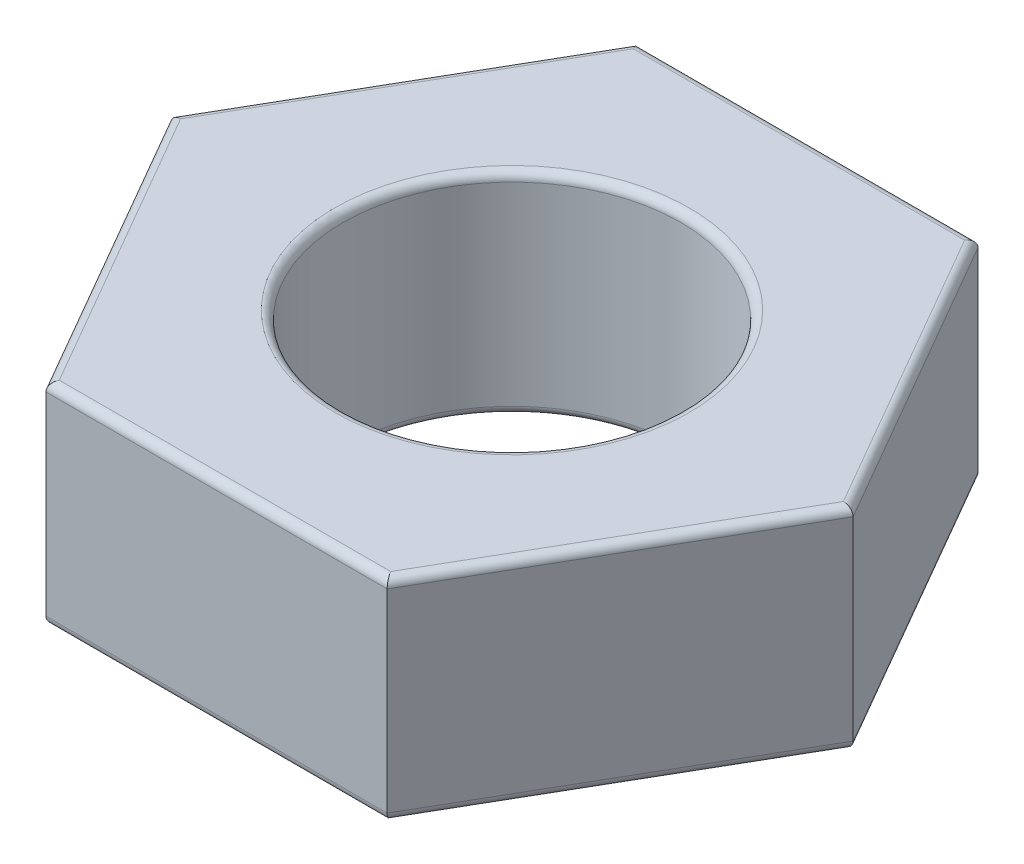
SolidWorks part; units mm, degrees
ref_plane "Front Plane" through (0, 0, 0) normal (0, 0, 1) x (1, 0, 0)
ref_plane "Top Plane" through (0, 0, 0) normal (0, 1, 0) x (1, 0, 0)
ref_plane "Right Plane" through (0, 0, 0) normal (1, 0, 0) x (0, 0, -1)
sketch "Sketch1" plane through (0, 0, 0) normal (0, 1, 0) x (1, 0, 0)
  line L1 (2.0207, -3.5) -> (4.0415, 0)
  line L2 (4.0415, 0) -> (2.0207, 3.5)
  line L3 (2.0207, 3.5) -> (-2.0207, 3.5)
  line L4 (-2.0207, 3.5) -> (-4.0415, 0)
  line L5 (-4.0415, 0) -> (-2.0207, -3.5)
  line L6 (-2.0207, -3.5) -> (2.0207, -3.5)
  circle A0 centre (0, 0) radius 3.5 construction
  circle A1 centre (0, 0) radius 2
  dimension "D1" = 7
  dimension "D2" = 4
extrude "Boss-Extrude1" add sketch "Sketch1" along normal blind 2.5
fillet "Fillet1" radius 0.1 14 edges at (0, 0, 2) (3.0311, 0, 1.75) (3.0311, 0, -1.75) (0, 0, -3.5) (-3.0311, 0, -1.75) (-3.0311, 0, 1.75) (0, 0, 3.5) (0, 2.5, 2) (-3.0311, 2.5, 1.75) (-3.0311, 2.5, -1.75) (0, 2.5, -3.5) (3.0311, 2.5, -1.75) (3.0311, 2.5, 1.75) (0, 2.5, 3.5)
